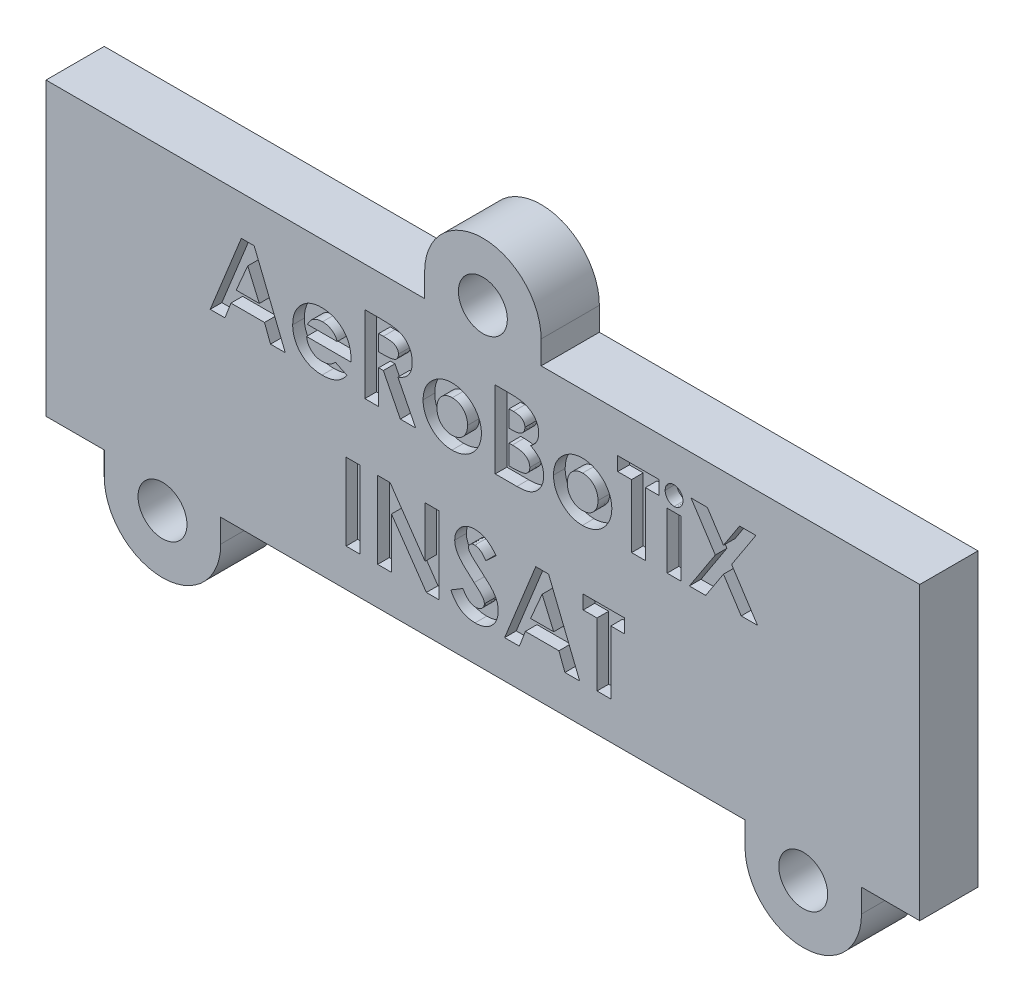
SolidWorks part; units mm, degrees
material "Balsa"
ref_plane "Plan de face" through (0, 0, 0) normal (0, 0, 1) x (1, 0, 0)
ref_plane "Plan de dessus" through (0, 0, 0) normal (0, 1, 0) x (1, 0, 0)
ref_plane "Plan de droite" through (0, 0, 0) normal (1, 0, 0) x (0, 0, -1)
sketch "Esquisse1" plane through (0, 0, 0) normal (0, 0, 1) x (1, 0, 0)
  line L1 (37.5, -12.5) -> (-37.5, -12.5)
  line L2 (37.5, -12.5) -> (37.5, 12.5)
  line L3 (37.5, 12.5) -> (-37.5, 12.5)
  line L4 (-37.5, -12.5) -> (-37.5, 12.5)
  line L5 (37.5, -12.5) -> (-37.5, 12.5) construction
  line L6 (37.5, 12.5) -> (-37.5, -12.5) construction
  point P0 (0, 0)
  dimension "D1" = 75
  dimension "D2" = 25
extrude "Boss.-Extru.1" add sketch "Esquisse1" along normal blind 5
sketch "Esquisse2" plane through (0, 0, 5) normal (0, 0, 1) x (1, 0, 0)
  line L0 (0, 0) -> (0, 14.5) construction
  line L1 (5, 12.5) -> (-5, 12.5)
  line L2 (37.5, 12.5) -> (-37.5, 12.5) construction
  line L3 (-5, 12.5) -> (-5, 14.5)
  line L4 (5, 12.5) -> (5, 14.5)
  line L5 (-22.5, -12.5) -> (-32.5, -12.5)
  line L6 (-37.5, -12.5) -> (37.5, -12.5) construction
  line L7 (-32.5, -12.5) -> (-32.5, -14.5)
  line L8 (-22.5, -14.5) -> (-22.5, -12.5)
  line L9 (22.5, -14.5) -> (22.5, -12.5)
  line L10 (32.5, -12.5) -> (32.5, -14.5)
  line L11 (22.5, -12.5) -> (32.5, -12.5)
  line L12 (-37.5, 12.5) -> (-37.5, -12.5) construction
  arc A0 (-5, 14.5) -> (5, 14.5) centre (0, 14.5) cw
  arc A2 (-32.5, -14.5) -> (-22.5, -14.5) centre (-27.5, -14.5) ccw
  arc A5 (32.5, -14.5) -> (22.5, -14.5) centre (27.5, -14.5) cw
  point P11 (0, 12.5)
  dimension "D3" = 5
  dimension "D4" = 5
  dimension "D5" = 2
  dimension "D6" = 2
  dimension "D7" = 5
extrude "Boss.-Extru.2" add sketch "Esquisse2" against normal blind 5
sketch "Esquisse3" plane through (0, 0, 5) normal (0, 0, 1) x (1, 0, 0)
  line L0 (-37.5, 2.5) -> (37.5, 2.5) construction
  line L2 (-37.5, 12.5) -> (-37.5, -12.5) construction
  line L3 (37.5, -12.5) -> (37.5, 12.5) construction
  line L4 (-5, 12.5) -> (-37.5, 12.5) construction
  text T0 "<b>AeRoBoTiX</b>\r\n<b>INSAT</b>" font "Century Gothic" height in points 25
  dimension "D1" = 10
extrude "Enlèv. mat.-Extru.1" cut sketch "Esquisse3" against normal blind 1
sketch "Esquisse4" plane through (0, 0, 5) normal (0, 0, 1) x (1, 0, 0)
  circle A0 centre (0, 14.5) radius 2.1
  circle A1 centre (27.5, -14.5) radius 2.1
  circle A2 centre (-27.5, -14.5) radius 2.1
  dimension "D1" = 4.2
extrude "Enlèv. mat.-Extru.2" cut sketch "Esquisse4" against normal through all
